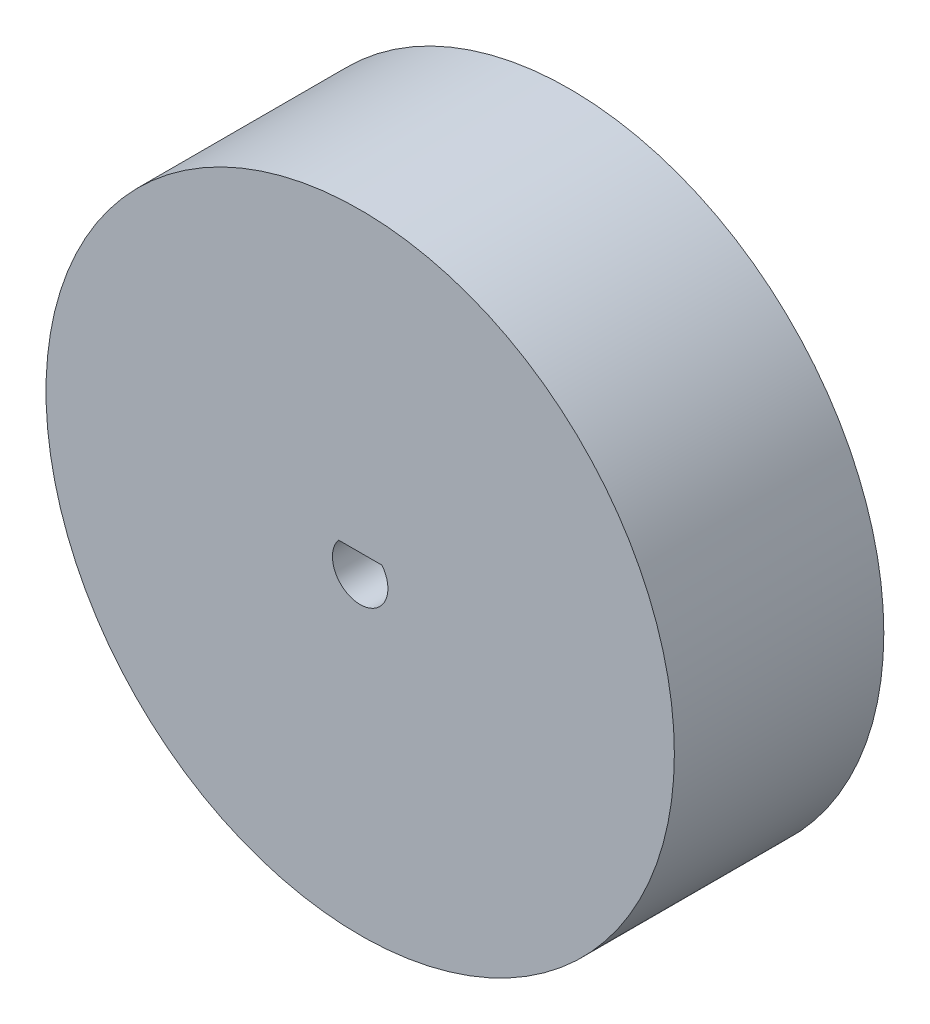
SolidWorks part; units mm, degrees
material "PET"
ref_plane "Front Plane" through (0, 0, 0) normal (0, 0, 1) x (1, 0, 0)
ref_plane "Top Plane" through (0, 0, 0) normal (0, 1, 0) x (1, 0, 0)
ref_plane "Right Plane" through (0, 0, 0) normal (1, 0, 0) x (0, 0, -1)
sketch "Sketch1" plane through (0, 0, 0) normal (0, 0, 1) x (1, 0, 0)
  circle A0 centre (0, 0) radius 30
  dimension "D1" = 60
extrude "Boss-Extrude1" add sketch "Sketch1" along normal blind 20
sketch "Sketch2" plane through (0, 0, 20) normal (0, 0, 1) x (1, 0, 0)
  line L0 (-2, 1.5) -> (2, 1.5) construction
  line L1 (-2.0736, 1.65) -> (2.0736, 1.65)
  arc A0 (-2, 1.5) -> (2, 1.5) centre (0, 0) ccw construction
  arc A1 (-2.0736, 1.65) -> (2.0736, 1.65) centre (0, 0) ccw
  dimension "D2" = 5
  dimension "D1" = 1.5
  dimension "D3" = 0.15
extrude "Cut-Extrude1" cut sketch "Sketch2" against normal through all
